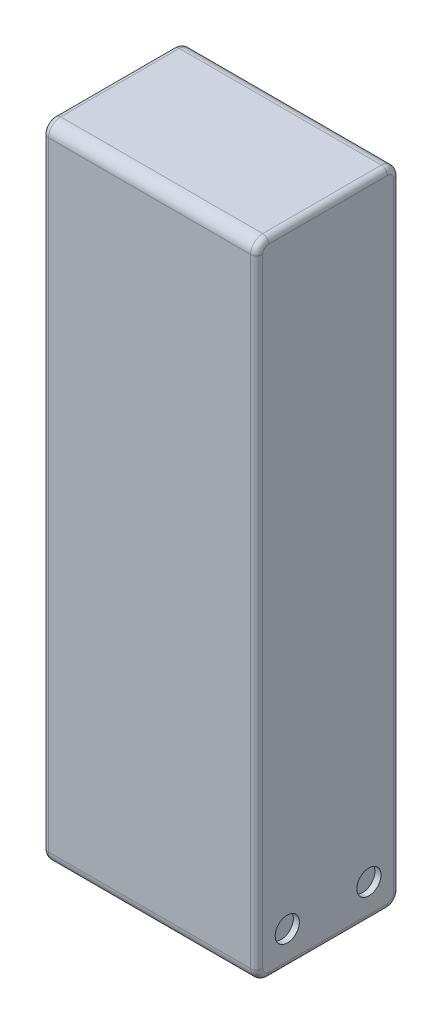
SolidWorks part; units mm, degrees
ref_plane "Front Plane" through (0, 0, 0) normal (0, 0, 1) x (1, 0, 0)
ref_plane "Top Plane" through (0, 0, 0) normal (0, 1, 0) x (1, 0, 0)
ref_plane "Right Plane" through (0, 0, 0) normal (1, 0, 0) x (0, 0, -1)
sketch "Sketch1" plane through (0, 0, 0) normal (0, 1, 0) x (1, 0, 0)
  line L1 (-22.5, -15) -> (22.5, -15)
  line L2 (-22.5, -15) -> (-22.5, 15)
  line L3 (-22.5, 15) -> (22.5, 15)
  line L4 (22.5, -15) -> (22.5, 15)
  line L5 (-22.5, -15) -> (22.5, 15) construction
  line L6 (-22.5, 15) -> (22.5, -15) construction
  point P0 (0, 0)
  dimension "D1" = 45
  dimension "D2" = 30
extrude "Boss-Extrude1" add sketch "Sketch1" along normal mid plane 135
fillet "Fillet1" radius 2.54 4 edges at (0, -67.5, 15) (0, -67.5, -15) (0, 67.5, 15) (0, 67.5, -15)
fillet "Fillet2" radius 1.27 16 edges at (-22.5, 66.7561, -14.2561) (-22.5, 67.5, 0) (-22.5, 66.7561, 14.2561) (-22.5, 0, 15) (-22.5, -66.7561, 14.2561) (-22.5, -67.5, 0) (-22.5, -66.7561, -14.2561) (22.5, 66.7561, -14.2561) (22.5, 67.5, 0) (22.5, 66.7561, 14.2561) (22.5, 0, 15) (22.5, -66.7561, 14.2561) (22.5, -67.5, 0) (22.5, -66.7561, -14.2561) (-22.5, 0, -15) (22.5, 0, -15)
sketch "Sketch2" plane through (22.5, 0, 0) normal (1, 0, 0) x (0, 0, -1)
  line L0 (-8.5725, -60.325) -> (8.5725, -60.325) construction
  circle A0 centre (8.5725, -60.325) radius 2.54
  circle A1 centre (-8.5725, -60.325) radius 2.54
  point P4 (0, -60.325)
  dimension "D3" = 5.08
  dimension "D1" = 17.145
  dimension "D2" = 60.325
extrude "Cut-Extrude1" cut sketch "Sketch2" against normal blind 1.27
